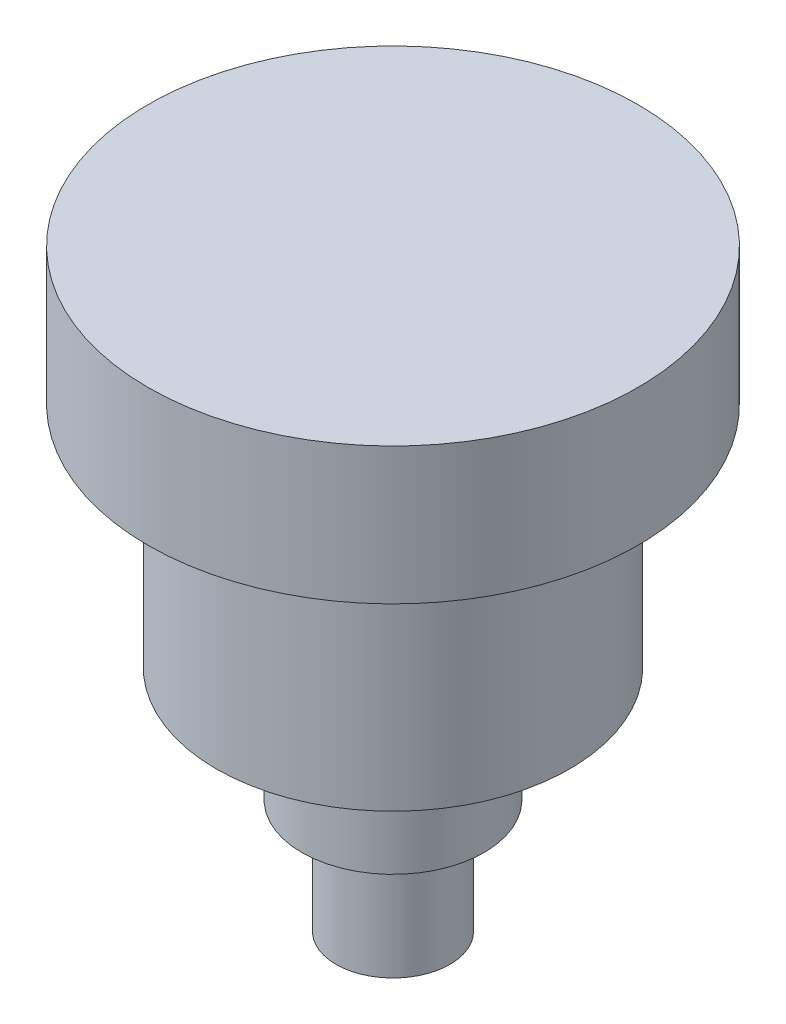
SolidWorks part; units mm, degrees
ref_plane "Front Plane" through (0, 0, 0) normal (0, 0, 1) x (1, 0, 0)
ref_plane "Top Plane" through (0, 0, 0) normal (0, 1, 0) x (1, 0, 0)
ref_plane "Right Plane" through (0, 0, 0) normal (1, 0, 0) x (0, 0, -1)
sketch "Sketch1" plane through (0, 0, 0) normal (0, 0, 1) x (1, 0, 0)
  line L0 (0, 35.15) -> (0, 0) construction
  line L1 (0, 0) -> (2.5, 0)
  line L2 (2.5, 0) -> (2.5, 5)
  line L3 (2.5, 5) -> (4, 5)
  line L4 (4, 5) -> (4, 10)
  line L5 (4, 10) -> (5, 10)
  line L6 (5, 10) -> (5, 10.05)
  line L7 (5, 10.05) -> (7.75, 10.05)
  line L8 (7.75, 10.05) -> (7.75, 20.05)
  line L9 (7.75, 20.05) -> (10.75, 20.05)
  line L10 (10.75, 20.05) -> (10.75, 26.05)
  line L11 (10.75, 26.05) -> (0, 26.05)
  line L12 (0, 26.05) -> (0, 0)
  dimension "D1" = 2.5
  dimension "D2" = 5
  dimension "D3" = 4
  dimension "D4" = 5
  dimension "D5" = 5
  dimension "D6" = 0.05
  dimension "D7" = 7.75
  dimension "D8" = 10
  dimension "D9" = 6
  dimension "D10" = 10.75
revolve "Revolve1" add sketch "Sketch1" angle 360 about L0
